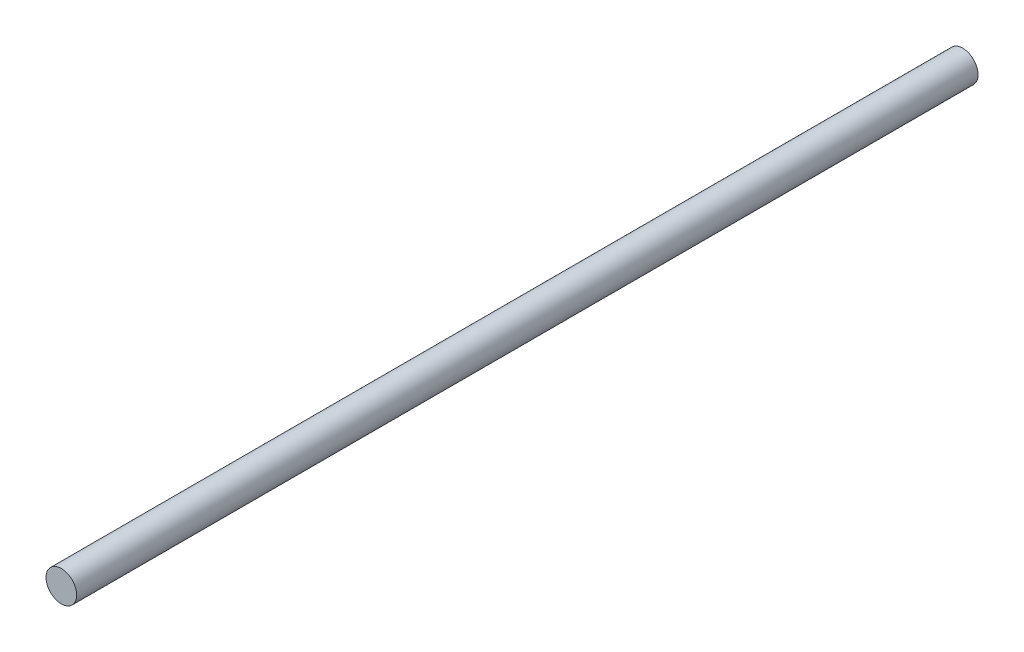
SolidWorks part; units mm, degrees
ref_plane "Front Plane" through (0, 0, 0) normal (0, 0, 1) x (1, 0, 0)
ref_plane "Top Plane" through (0, 0, 0) normal (0, 1, 0) x (1, 0, 0)
ref_plane "Right Plane" through (0, 0, 0) normal (1, 0, 0) x (0, 0, -1)
sketch "Sketch1" plane through (0, 0, 0) normal (0, 0, 1) x (1, 0, 0)
  circle A0 centre (0, 0) radius 4
  dimension "D1" = 8
extrude "Boss-Extrude1" add sketch "Sketch1" along normal blind 235
